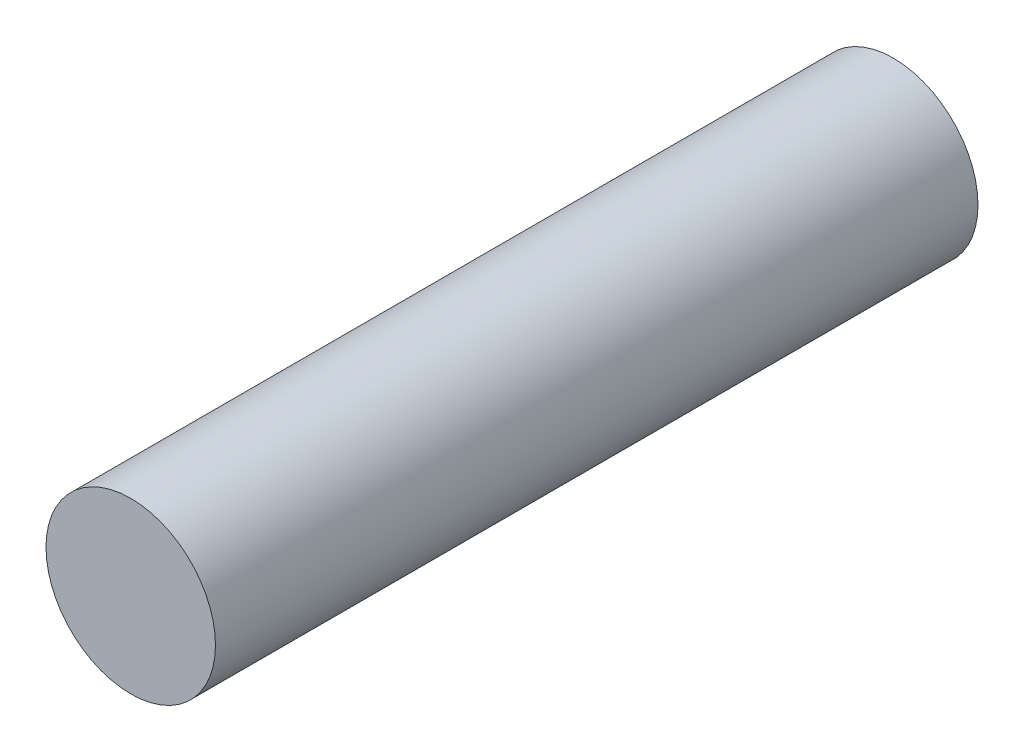
SolidWorks part; units mm, degrees
ref_plane "정면" through (0, 0, 0) normal (0, 0, 1) x (1, 0, 0)
ref_plane "윗면" through (0, 0, 0) normal (0, 1, 0) x (1, 0, 0)
ref_plane "우측면" through (0, 0, 0) normal (1, 0, 0) x (0, 0, -1)
sketch "스케치1" plane through (0, 0, 0) normal (0, 0, 1) x (1, 0, 0)
  circle A0 centre (0, 0) radius 3
  dimension "D1" = 6
extrude "보스-돌출1" add sketch "스케치1" along normal blind 27
